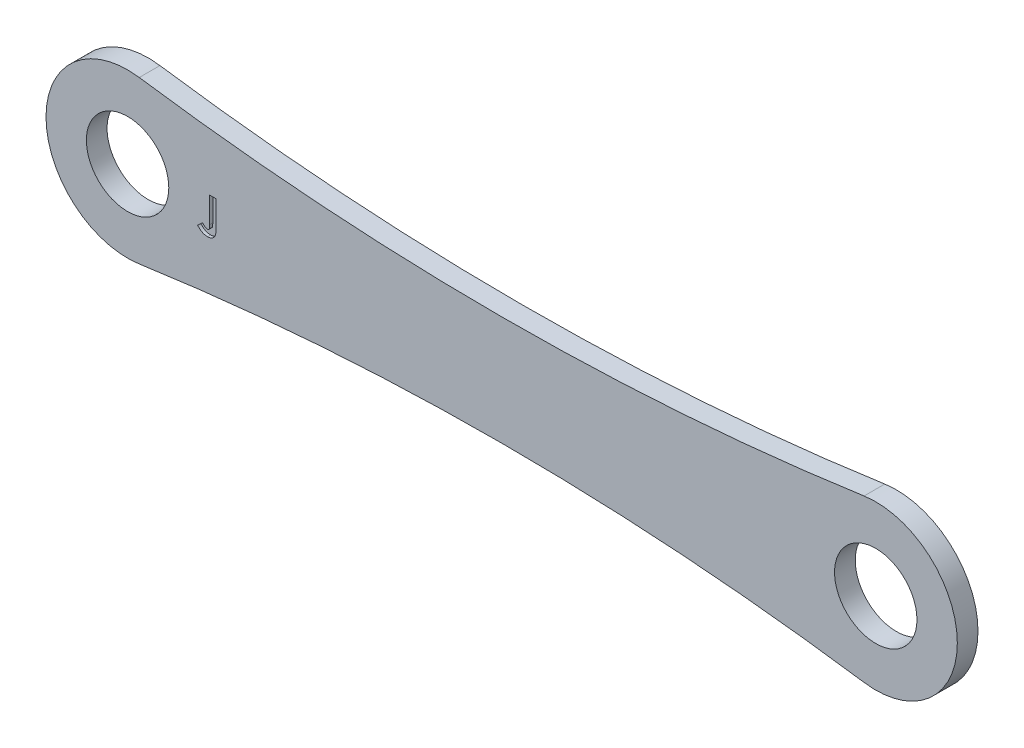
SolidWorks part; units mm, degrees
ref_plane "Plan de face" through (0, 0, 0) normal (1, 0, 0) x (0, 1, 0)
ref_plane "Plan de dessus" through (0, 0, 0) normal (0, 0, 1) x (0, 1, 0)
ref_plane "Plan de droite" through (0, 0, 0) normal (0, 1, 0) x (-1, 0, 0)
sketch "Esquisse1" plane through (0, 0, 0) normal (0, 0, 1) x (0, 1, 0)
  line L0 (0, 0) -> (0, 72.36) construction
  circle A0 centre (0, 72.36) radius 3.985
  circle A1 centre (0, 0) radius 3.985
  circle A2 centre (0, 0) radius 7.89
  circle A3 centre (0, 72.36) radius 7.89
  arc A4 (-7.8088, 71.2312) -> (-7.8088, 1.1288) centre (-250.2886, 36.18) cw
  arc A5 (7.8088, 71.2312) -> (7.8088, 1.1288) centre (250.2886, 36.18) ccw
  dimension "D2" = 7.97
  dimension "D3" = 15.78
  dimension "D4" = 245
  dimension "D1" = 72.36
extrude "Boss.-Extru.1" add sketch "Esquisse1" along normal blind 2
sketch "Esquisse2" plane through (0, 0, 2) normal (0, 0, 1) x (1, 0, 0)
  text T0 "<b>J</b>"
extrude "Enlèv. mat.-Extru.1" cut sketch "Esquisse2" against normal blind 0.3
